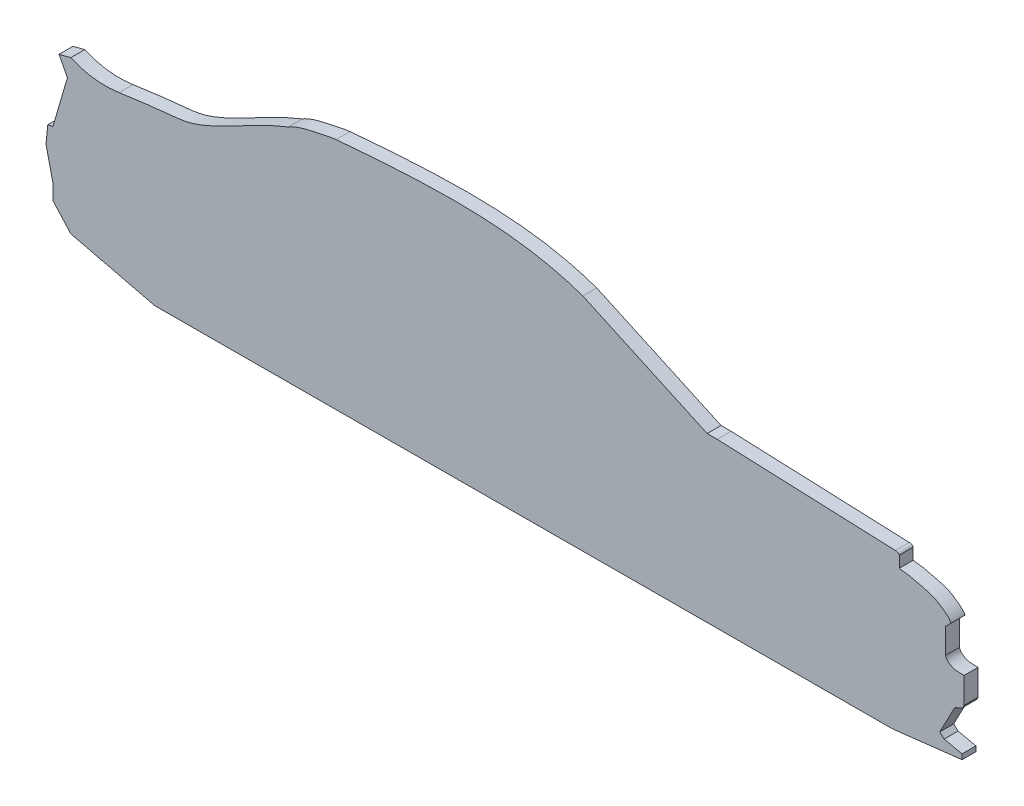
SolidWorks part; units mm, degrees
ref_plane "Front Plane" through (0, 0, 0) normal (0, 0, 1) x (1, 0, 0)
ref_plane "Top Plane" through (0, 0, 0) normal (0, 1, 0) x (1, 0, 0)
ref_plane "Right Plane" through (0, 0, 0) normal (1, 0, 0) x (0, 0, -1)
sketch "Sketch3" plane through (0, 0, 0) normal (0, 0, 1) x (1, 0, 0)
  line L0 (312.5, 297) -> (1562.5, 297) construction
  line L1 (126.1542, 61.5939) -> (154.5663, 48.576)
  line L2 (154.5663, 48.576) -> (156.8747, 48.576)
  line L3 (212.8427, 14.2784) -> (212.8427, 13.1195)
  line L4 (156.8747, 48.576) -> (197.5905, 46.9297)
  line L5 (198.4878, 46.4398) -> (198.4878, 43.8451)
  line L6 (210.3465, 38.9222) -> (209.0964, 37.6721)
  line L7 (208.7532, 15.1667) -> (212.8427, 14.2784)
  line L10 (28.2442, 10.7403) -> (9.0785, 15.3707)
  line L15 (9.0785, 15.3707) -> (5.0001, 19.8806)
  line L16 (5.0001, 19.8806) -> (5.0001, 23.3781)
  line L17 (5.0001, 23.3781) -> (3.4081, 30.2754)
  line L18 (3.4081, 30.2754) -> (3.8115, 34.3395)
  line L19 (3.8115, 34.3395) -> (5.0001, 34.6139)
  line L20 (5.0001, 34.6139) -> (8.3049, 45.881)
  line L21 (8.3049, 45.881) -> (6.3896, 49.5718)
  line L22 (6.3896, 49.5718) -> (9.0785, 50.2521)
  line L23 (209.0964, 37.6721) -> (209.0964, 31.9069)
  line L24 (213.312, 30.0524) -> (213.312, 24.1361)
  line L25 (211.0158, 22.3038) -> (207.7566, 16.0946)
  line L26 (207.7566, 16.0946) -> (208.7532, 15.1667)
  line L27 (212.8427, 13.1195) -> (196.9843, 11.2857)
  line L28 (28.2442, 10.7403) -> (196.9843, 11.2857)
  spline S0 degree 3 poles (197.5905, 46.9297) (197.9582, 46.9895) (198.3362, 46.7695) (198.4878, 46.4398) knots 0 0 0 0 1 1 1 1
  spline S4 degree 3 poles (198.4878, 43.8451) (200.1541, 43.737) (202.765, 43.083) (206.183, 42.2562) (208.5287, 40.8311) (209.9104, 39.7427) (210.3465, 38.9222) knots 0 0 0 0 0.376789 0.614455 0.789915 1 1 1 1
  spline S5 degree 2 poles (9.0785, 50.2521) (14.2515, 47.9792) (20.1338, 48.8537) knots 0 0 0 1 1 1
  spline S7 degree 3 poles (69.7482, 64.3585) (69.9738, 64.3795) (71.3142, 64.5016) (74.0038, 64.7164) (79.1087, 65.1366) (96.6448, 66.1821) (113.2269, 66.1038) (126.1542, 61.5939) knots 0.026005 0.026005 0.026005 0.026005 0.037654 0.09523 0.164779 0.301014 1 1 1 1
  spline S8 degree 3 poles (209.0964, 31.9069) (209.2323, 31.1985) (209.9206, 30.6804) (211.4276, 29.9869) (212.5209, 30.0888) (213.312, 30.0524) knots 0 0 0 0 0.389815 0.49905 1 1 1 1
  spline S9 degree 3 poles (213.312, 24.1361) (213.2086, 23.8622) (212.9573, 23.3801) (212.3083, 23.0293) (211.6067, 22.8604) (211.1836, 22.6234) (211.0158, 22.3038) knots 0 0 0 0 0.29515 0.505509 0.707214 1 1 1 1
  spline S10 degree 3 poles (20.1338, 48.8537) (23.947, 49.456) (28.8452, 49.9698) (34.0928, 50.5052) (36.0039, 50.8804) (39.5982, 51.9069) (47.1759, 55.732) (54.085, 59.5062) (58.7826, 61.3879) knots 0 0 0 0 0.281455 0.359727 0.384534 0.423485 0.632085 1 1 1 1
  spline S11 degree 3 poles (58.7826, 61.3879) (59.9553, 62.0984) (61.6812, 62.6757) (64.0272, 63.2668) (66.6444, 63.7787) (68.8081, 64.3094) (70.4249, 64.4202) knots 0 0 0 0 0.338684 0.447561 0.600476 1 1 1 1
ref_plane "Plane1" through (0, 0, -6) normal (0, 0, -1) x (-1, 0, 0)
ref_plane "Plane2" through (0, 0, 76) normal (0, 0, 1) x (1, 0, 0)
extrude "Boss-Extrude2" add sketch "Sketch3" along normal blind 3.18 contours S11 S10 S5 L22 L21 L20 L19 L18 L17 L16 L15 L10 L28 L27 L3 L7 L26 L25 S9 L24 S8 L23 L6 S4 L5 S0 L4 L2 L1 S7
